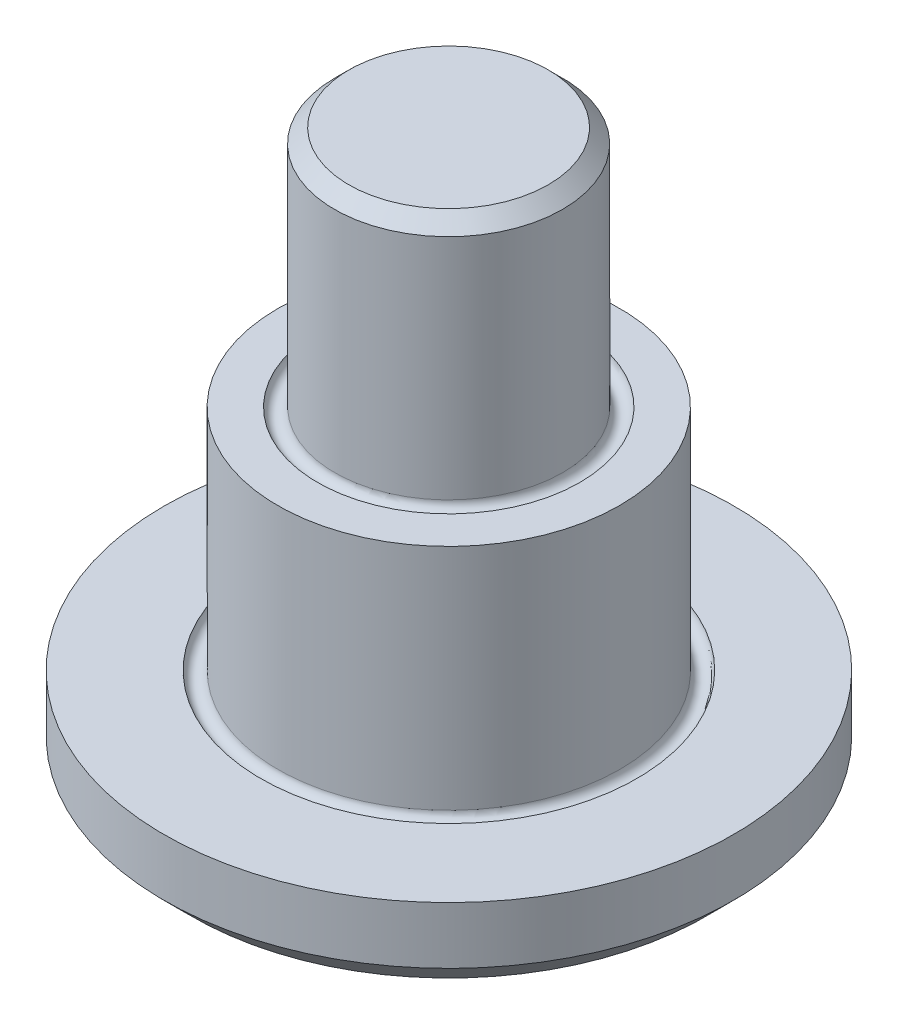
SolidWorks part; units mm, degrees
ref_plane "Plan1" through (0, 0, 0) normal (0, 0, 1) x (1, 0, 0)
ref_plane "Plan2" through (0, 0, 0) normal (0, 1, 0) x (1, 0, 0)
ref_plane "Plan3" through (0, 0, 0) normal (1, 0, 0) x (0, 0, -1)
ref_plane "Plan4" through (0, 0.0318, 805.747) normal (0, 0, -1) x (-1, 0, 0)
sketch "Esquisse1" plane through (0, 0.0318, 805.747) normal (0, 0, -1) x (-1, 0, 0)
  line L0 (-2032.314, 595.9713) -> (-2023.3133, 595.9648)
  line L1 (-2023.3133, 595.9648) -> (-2023.2992, 615.4648)
  line L2 (-2023.2992, 615.4648) -> (-2026.7996, 615.4673)
  line L3 (-2026.7996, 615.4673) -> (-2027.2996, 614.9681)
  line L4 (-2027.2996, 614.9681) -> (-2027.3053, 606.9681)
  line L5 (-2027.9053, 606.9681) -> (-2029.3053, 606.9691)
  line L6 (-2029.3053, 606.9691) -> (-2029.3111, 598.948)
  line L7 (-2029.9104, 598.9696) -> (-2033.3111, 598.972)
  line L8 (-2033.3111, 598.972) -> (-2033.3126, 596.9713)
  line L9 (-2033.3126, 596.9713) -> (-2032.314, 595.9713)
  line L10 (-2023.3133, 595.9642) -> (-2023.2992, 615.4655) construction
  arc A0 (-2027.3053, 606.9681) -> (-2027.9053, 606.9681) centre (-2027.6053, 606.9683) cw
  arc A1 (-2029.3111, 598.948) -> (-2029.9104, 598.9696) centre (-2029.6104, 598.9692) cw
  dimension "D1" = 0.3
  dimension "D2" = 0.3
  dimension "D3" = 3
  dimension "D4" = 11
  dimension "D5" = 8.5
  dimension "D6" = 8
  dimension "D7" = 12
  dimension "D8" = 20
  dimension "D9" = 0.5
  dimension "D10" = 1
  dimension "D11" = 45
  dimension "D12" = 45
revolve "Base-Révolution" add sketch "Esquisse1" angle 360 about L10
